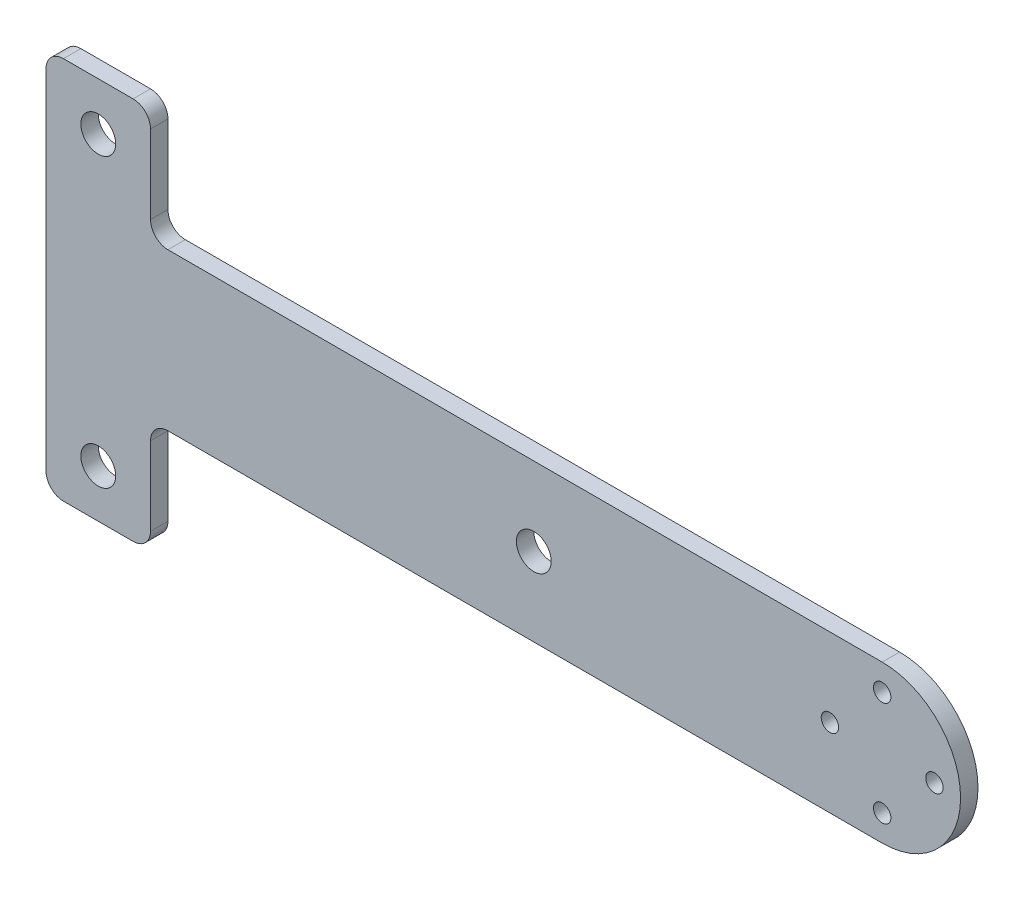
SolidWorks part; units mm, degrees
ref_plane "前视基准面" through (0, 0, 0) normal (0, 0, 1) x (1, 0, 0)
ref_plane "上视基准面" through (0, 0, 0) normal (0, 1, 0) x (1, 0, 0)
ref_plane "右视基准面" through (0, 0, 0) normal (1, 0, 0) x (0, 0, -1)
sketch "草图1" plane through (0, 0, 0) normal (0, 0, 1) x (1, 0, 0)
  line L0 (41.2764, 0.1457) -> (41.2764, 6.1457)
  line L1 (41.2764, -8.8543) -> (-42.7236, -8.8543)
  line L2 (41.2764, 9.1457) -> (-42.7236, 9.1457)
  line L3 (-42.7236, 9.1457) -> (-42.7236, 22.1457)
  line L4 (-42.7236, 22.1457) -> (-54.7236, 22.1457)
  line L5 (-54.7236, 22.1457) -> (-54.7236, -21.8543)
  line L6 (-54.7236, -21.8543) -> (-42.7236, -21.8543)
  line L7 (-42.7236, -21.8543) -> (-42.7236, -8.8543)
  circle A1 centre (1.2764, 0.1457) radius 2
  circle A2 centre (-48.7236, 16.6457) radius 2
  circle A3 centre (-48.7236, -16.3543) radius 2
  circle A4 centre (41.2764, 6.1457) radius 1
  circle A5 centre (47.2764, 0.1457) radius 1
  circle A6 centre (41.2764, -5.8543) radius 1
  circle A7 centre (35.2764, 0.1457) radius 1
  circle A8 centre (41.2764, 0.1457) radius 9 construction
  arc A9 (41.2764, 9.1457) -> (41.2764, -8.8543) centre (41.2764, 0.1457) cw
  dimension "D1" = 4
  dimension "D3" = 2
  dimension "D5" = 33
  dimension "D2" = 6
  dimension "D6" = 13
  dimension "D7" = 12
  dimension "D8" = 90
  dimension "D9" = 6
  dimension "D4" = 4
extrude "凸台-拉伸1" add sketch "草图1" along normal blind 2
fillet "圆角1" radius 2 6 edges at (-42.7236, 9.1457, 1) (-42.7236, 22.1457, 1) (-54.7236, 22.1457, 1) (-42.7236, -8.8543, 1) (-42.7236, -21.8543, 1) (-54.7236, -21.8543, 1)
